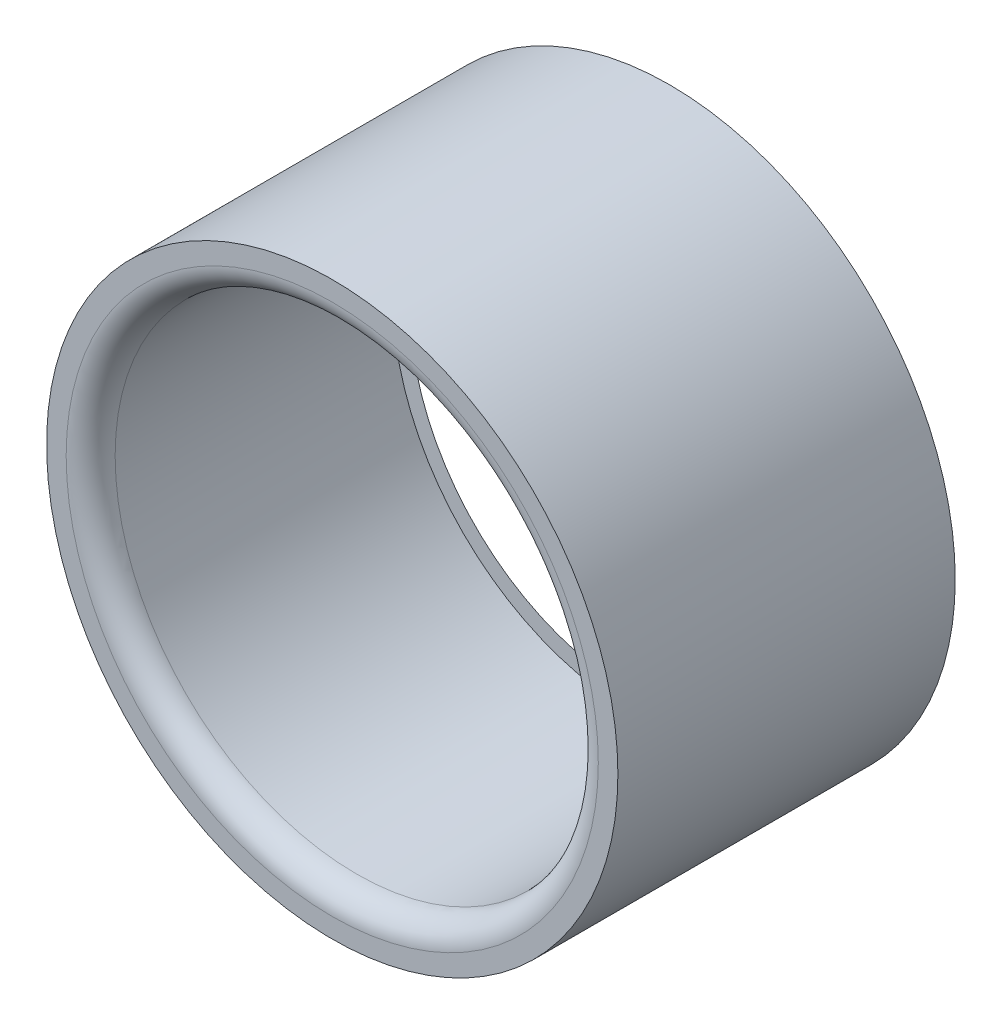
SolidWorks part; units mm, degrees
ref_plane "Front Plane" through (0, 0, 0) normal (0, 0, 1) x (1, 0, 0)
ref_plane "Top Plane" through (0, 0, 0) normal (0, 1, 0) x (1, 0, 0)
ref_plane "Right Plane" through (0, 0, 0) normal (1, 0, 0) x (0, 0, -1)
sketch "Sketch1" plane through (0, 0, 0) normal (0, 0, 1) x (1, 0, 0)
  circle A0 centre (0, 0) radius 29.75
  circle A1 centre (0, 0) radius 31
  dimension "D1" = 59.5
  dimension "D2" = 62
extrude "Boss-Extrude1" add sketch "Sketch1" along normal blind 29 contours A0 | A1
sketch "Sketch2" plane through (0, 0, 29) normal (0, 0, 1) x (1, 0, 0)
  circle A0 centre (0, 0) radius 29.6
  circle A1 centre (0, 0) radius 32.5
  dimension "D1" = 59.2
  dimension "D2" = 65
extrude "Boss-Extrude3" add sketch "Sketch2" against normal blind 35 contours A1 | A0
fillet "Fillet2" radius 2 1 edges at (29.6, 0, -6)
sketch "Sketch3" plane through (0, 0, 29) normal (0, 0, 1) x (1, 0, 0)
  circle A0 centre (0, 0) radius 32.5
extrude "Cut-Extrude1" cut sketch "Sketch3" against normal blind 3.5
sketch "Sketch4" plane through (0, 0, 25.5) normal (0, 0, 1) x (1, 0, 0)
  circle A0 centre (0, 0) radius 29.6
  circle A1 centre (0, 0) radius 27.5
  dimension "D1" = 55
extrude "Boss-Extrude4" add sketch "Sketch4" against normal blind 15
sketch "Sketch5" plane through (0, 0, 10.5) normal (0, 0, -1) x (-1, 0, 0)
  circle A0 centre (0, 0) radius 29.6
extrude "Cut-Extrude2" cut sketch "Sketch5" against normal blind 33
sketch "Sketch6" plane through (0, 0, 25.5) normal (0, 0, 1) x (1, 0, 0)
  circle A0 centre (0, 0) radius 29.6
  circle A1 centre (0, 0) radius 35
  dimension "D1" = 70
extrude "Boss-Extrude5" add sketch "Sketch6" against normal blind 37
sketch "Sketch7" plane through (0, 0, 0) normal (0, 1, 0) x (1, 0, 0)
  line L0 (0, 15.8301) -> (0, -31.5572)
  line L2 (35, 11.5) -> (-35, 11.5) construction
  line L3 (-27.5, 11.5) -> (-35, 15.8301)
  line L4 (-35, 11.5) -> (-35, 15.8301)
  line L5 (-35, 11.5) -> (-27.5, 11.5)
  dimension "D2" = 30
revolve "Revolve1" add sketch "Sketch7" angle 360 about L0
fillet "Fillet3" radius 3 1 edges at (29.6, 0, 25.5)
